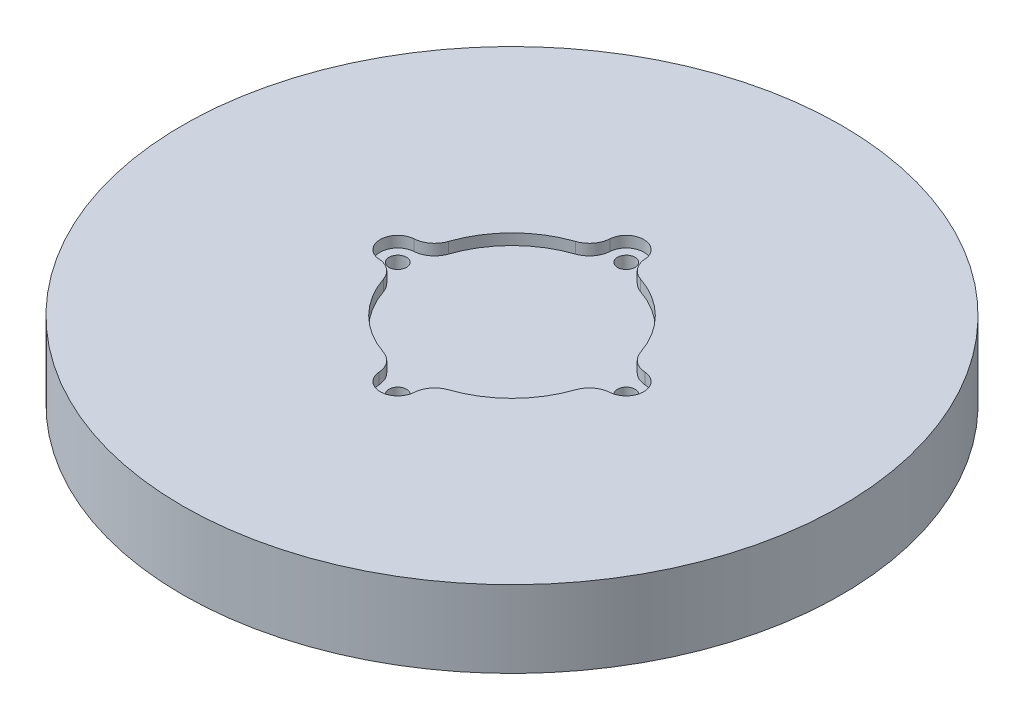
SolidWorks part; units mm, degrees
ref_plane "Front Plane" through (0, 0, 0) normal (0, 0, 1) x (1, 0, 0)
ref_plane "Top Plane" through (0, 0, 0) normal (0, 1, 0) x (1, 0, 0)
ref_plane "Right Plane" through (0, 0, 0) normal (1, 0, 0) x (0, 0, -1)
sketch "Sketch1" plane through (0, 0, 0) normal (0, 1, 0) x (1, 0, 0)
  circle A0 centre (0, 0) radius 150
extrude "Boss-Extrude1" add sketch "Sketch1" along normal blind 35
sketch "Sketch2" plane through (0, 0, 0) normal (0, -1, 0) x (1, 0, 0)
  line L0 (0, 0) -> (52, 0)
  circle A0 centre (52, 0) radius 4
  circle A1 centre (0, -52) radius 4
  circle A2 centre (-52, 0) radius 4
  circle A3 centre (0, 52) radius 4
  point P13 (0, 0)
  dimension "D1" = 4
extrude "Cut-Extrude1" cut sketch "Sketch2" against normal blind 30 contours A3 | A2 | A0 | A1
sketch "Sketch3" plane through (0, 35, 0) normal (0, 1, 0) x (1, 0, 0)
  line L0 (52, -8) -> (45.44, -8)
  line L1 (52, 8) -> (45.44, 8)
  line L2 (-8, -52) -> (-8, -45.44)
  line L3 (8, -52) -> (8, -45.44)
  line L4 (-52, 8) -> (-45.44, 8)
  line L5 (-52, -8) -> (-45.44, -8)
  line L6 (8, 52) -> (8, 45.44)
  line L7 (-8, 52) -> (-8, 45.44)
  circle A0 centre (0, 0) radius 46.1389
  circle A1 centre (52, 0) radius 8
  circle A2 centre (0, -52) radius 8
  circle A3 centre (-52, 0) radius 8
  circle A4 centre (0, 52) radius 8
  point P31 (0, 0)
  dimension "D1" = 4
extrude "Cut-Extrude2" cut sketch "Sketch3" against normal blind 5
fillet "Fillet1" radius 10 8 edges at (-45.44, 32.5, 8) (-8, 32.5, 45.44) (8, 32.5, 45.44) (45.44, 32.5, 8) (45.44, 32.5, -8) (8, 32.5, -45.44) (-8, 32.5, -45.44) (-45.44, 32.5, -8)
